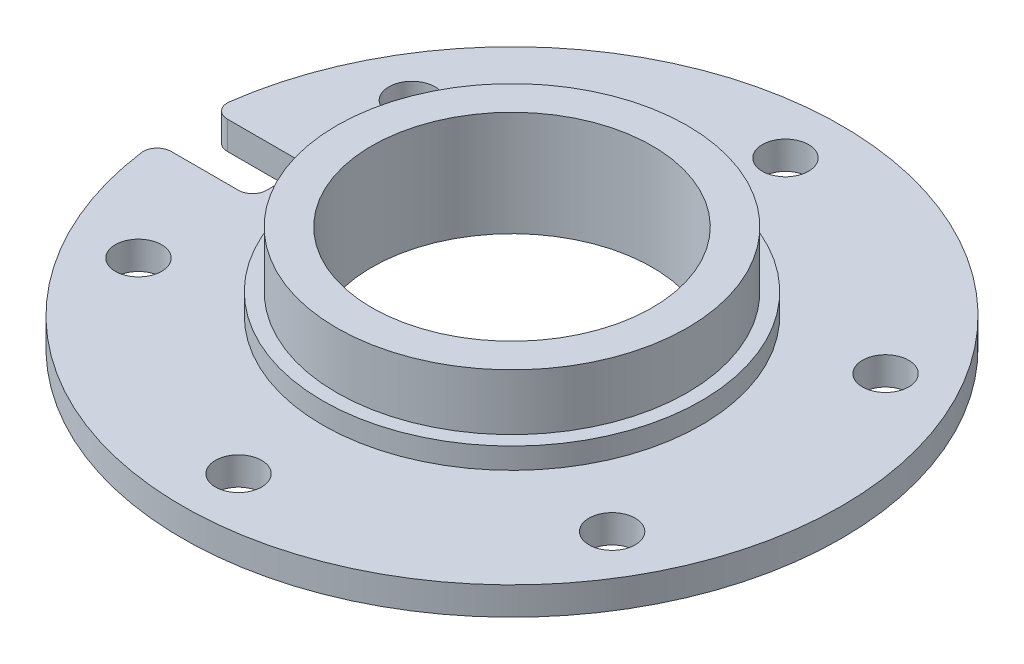
SolidWorks part; units mm, degrees
material "6061 合金"
ref_plane "前视基准面" through (0, 0, 0) normal (0, 0, 1) x (1, 0, 0)
ref_plane "上视基准面" through (0, 0, 0) normal (0, 1, 0) x (1, 0, 0)
ref_plane "右视基准面" through (0, 0, 0) normal (1, 0, 0) x (0, 0, -1)
other "Configuration Table"
sketch "草图1" plane through (0, 0, 0) normal (0, 1, 0) x (1, 0, 0)
  circle A0 centre (0, 0) radius 23.5
  circle A1 centre (0, 0) radius 10
  circle A2 centre (0, 0) radius 19.5 construction
  circle A3 centre (0, 19.5) radius 1
  circle A4 centre (16.8875, 9.75) radius 1
  circle A5 centre (16.8875, -9.75) radius 1
  circle A6 centre (0, -19.5) radius 1
  circle A7 centre (-16.8875, -9.75) radius 1
  circle A8 centre (-16.8875, 9.75) radius 1
  point P20 (0, 0)
  dimension "D1" = 47
  dimension "D2" = 20
  dimension "D3" = 39
  dimension "D4" = 2
  dimension "D5" = 6
extrude "凸台-拉伸1" add sketch "草图1" along normal blind 2
sketch "草图2" plane through (0, 2, 0) normal (0, 1, 0) x (1, 0, 0)
  circle A1 centre (0, 0) radius 10
  circle A2 centre (0, 0) radius 12.5
  circle A3 centre (0, 0) radius 10 construction
  dimension "D1" = 25
extrude "凸台-拉伸2" add sketch "草图2" along normal blind 5.5
sketch "草图3" plane through (0, 2, 0) normal (0, 1, 0) x (1, 0, 0)
  circle A0 centre (0, 0) radius 12.5
  circle A1 centre (0, 0) radius 12.5 construction
  circle A2 centre (0, 0) radius 13.5
  dimension "D1" = 1
extrude "凸台-拉伸3" add sketch "草图3" along normal blind 1.5
sketch "草图4" plane through (0, 0, 0) normal (0, -1, 0) x (1, 0, 0)
  line L0 (0, 0) -> (-23.5, 0) construction
  line L2 (-24.257, 2) -> (-16.5, 2)
  line L3 (-24.257, 2) -> (-24.257, -2)
  line L4 (-24.257, -2) -> (-16.5, -2)
  line L5 (-16.5, 2) -> (-16.5, -2)
  circle A0 centre (0, 0) radius 23.5 construction
  dimension "D1" = 7
  dimension "D2" = 2
extrude "切除-拉伸1" cut sketch "草图4" against normal blind 10
fillet "圆角1" radius 1 4 edges at (-23.4147, 1, 2) (-23.4147, 1, -2) (-16.5, 1, 2) (-16.5, 1, -2)
hole_wizard "M4 螺纹孔1" positions "草图14" profile "草图13" tap size "M4" standard "GB" end condition through all
sketch "草图14" plane through (0, 0, 0) normal (0, -1, 0) x (-1, 0, 0)
  point P0 (0, 19.5)
  point P3 (-16.8875, 9.75)
  point P6 (-16.8875, -9.75)
  point P9 (0, -19.5)
  point P12 (16.8875, -9.75)
  point P15 (16.8875, 9.75)
sketch "草图13" plane through (0, 0, -19.5) normal (1, 0, 0) x (0, 0, -1)
  line L0 (0, 0) -> (0, 7.5)
  line L1 (0, 7.5) -> (1.65, 7.5)
  line L2 (1.65, 7.5) -> (1.65, 0)
  line L5 (1.65, 0) -> (0, 0)
  line L11 (0, -6.35) -> (0, 107.95) construction
  dimension "通孔螺纹孔钻头直径" = 3.3
  dimension "通孔螺纹孔钻头深度" = 7.5
cosmetic thread "孔螺纹线7" parameters "D2"=4
cosmetic thread "孔螺纹线8" parameters "D2"=4
cosmetic thread "孔螺纹线9" parameters "D2"=4
cosmetic thread "孔螺纹线10" parameters "D2"=4
cosmetic thread "孔螺纹线11" parameters "D2"=4
cosmetic thread "孔螺纹线12" parameters "D2"=4
